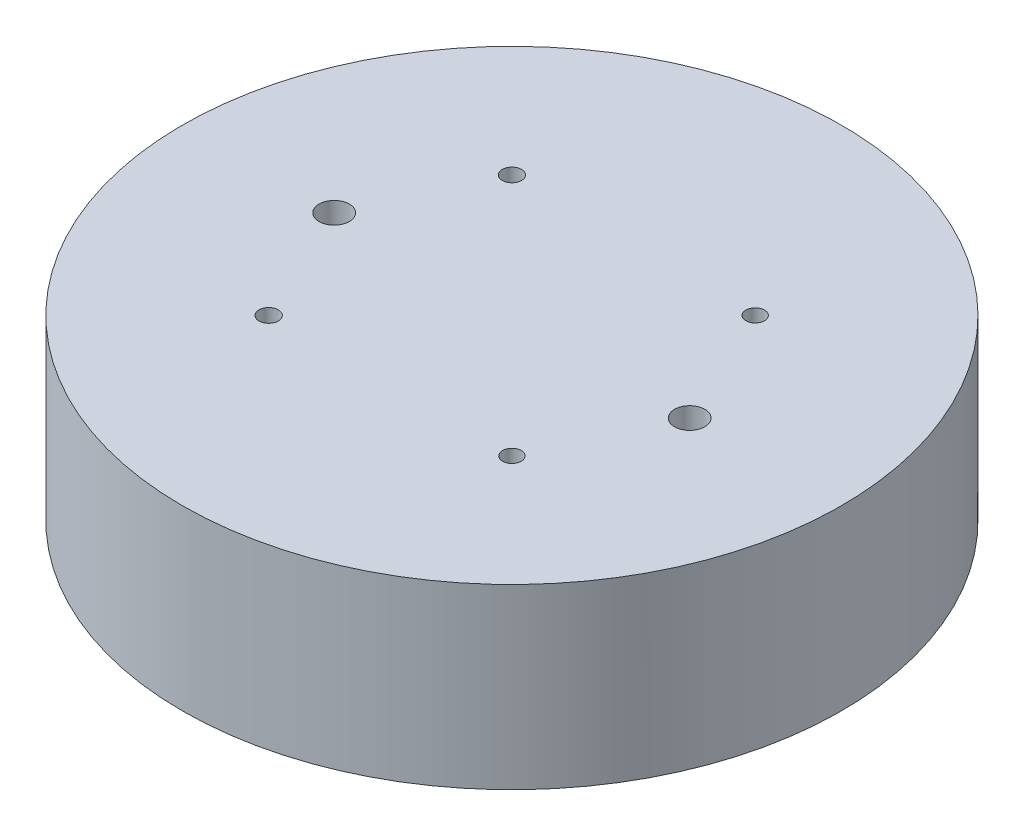
SolidWorks part; units mm, degrees
ref_plane "Front Plane" through (0, 0, 0) normal (0, 0, 1) x (1, 0, 0)
ref_plane "Top Plane" through (0, 0, 0) normal (0, 1, 0) x (1, 0, 0)
ref_plane "Right Plane" through (0, 0, 0) normal (1, 0, 0) x (0, 0, -1)
sketch "Sketch2" plane through (0, 0, 0) normal (0, 1, 0) x (1, 0, 0)
  line L0 (0, 0) -> (0, 56.515)
  circle A0 centre (0, 0) radius 51.435
  circle A1 centre (0, 0) radius 56.515
  circle A2 centre (0, 0) radius 47.2017
  circle A3 centre (0, 0) radius 42.1217
  dimension "D1" = 14.3933
  dimension "D2" = 5.08
  dimension "D3" = 4.2333
  dimension "D4" = 5.08
  dimension "D5" = 102.87
  dimension "D6" = 94.4033
extrude "Boss-Extrude1" add sketch "Sketch2" along normal blind 15.24 contours A1 A0 | A2 A3
sketch "Sketch3" plane through (0, 15.24, 0) normal (0, 1, 0) x (1, 0, 0)
  circle A0 centre (0, 0) radius 56.515
  dimension "D1" = 113.03
extrude "Boss-Extrude2" add sketch "Sketch3" along normal blind 15.24
sketch "Sketch4" plane through (0, 30.48, 0) normal (0, 1, 0) x (1, 0, 0)
  line L0 (0, 37.845) -> (0, -37.845) construction
  line L1 (37.845, 0) -> (-37.845, 0) construction
  line L2 (26.7605, 26.7605) -> (-26.7605, -26.7605) construction
  line L3 (-26.7605, 26.7605) -> (26.7605, -26.7605) construction
  circle A0 centre (0, 0) radius 37.845 construction
  circle A1 centre (0, 0) radius 29.5 construction
  circle A2 centre (20.8597, 20.8597) radius 1.6
  circle A3 centre (20.8597, -20.8597) radius 1.6
  circle A4 centre (-20.8597, -20.8597) radius 1.6588
  circle A5 centre (-20.8597, 20.8597) radius 1.651
  point P7 (0, 0)
  point P10 (0, 0)
  point P13 (0, 0)
  point P16 (0, 0)
  dimension "D1" = 75.69
  dimension "D2" = 59
  dimension "D3" = 45
  dimension "D4" = 45
  dimension "D5" = 3.2
  dimension "D6" = 3.2
  dimension "D7" = 3.3175
  dimension "D8" = 3.302
extrude "Cut-Extrude1" cut sketch "Sketch4" against normal through all both and the other way through all
sketch "Sketch5" plane through (0, 0, 0) normal (0, -1, 0) x (-1, 0, 0)
  line L0 (0, 0) -> (0, 29.5)
  line L1 (13.9476, 25) -> (-13.9476, 25)
  circle A1 centre (0, 0) radius 37.845
  circle A2 centre (0, 0) radius 29.5
  arc A3 (-13.9476, 54.7669) -> (13.9476, 54.7669) centre (0, 0) cw
  circle A4 centre (0, 0) radius 56.515 construction
  point P9 (0, 25)
  dimension "D1" = 75.69
  dimension "D2" = 59
  dimension "D3" = 25
  dimension "D4" = 31.515
ref_plane "Plane1" through (0, 0, -56.515) normal (0, 0, 1) x (1, 0, 0)
ref_plane "Plane3" through (0, 0, -47.244) normal (0, 0, 1) x (1, 0, 0)
ref_plane "Plane4" through (17.78, 0, 0) normal (1, 0, 0) x (0, 0, -1)
sketch "Sketch13" plane through (0, 0, -56.515) normal (0, 0, 1) x (1, 0, 0)
  line L0 (0, 0) -> (0, 32.5704) construction
sketch "Sketch14" plane through (0, 0, -56.515) normal (0, 0, 1) x (1, 0, 0)
  line L0 (0, 0) -> (0, 30.48) construction
  line L1 (-56.515, 0) -> (56.515, 0) construction
  line L2 (56.515, 30.48) -> (-56.515, 30.48) construction
  line L3 (0, 15.24) -> (-5.7214, 15.24) construction
  circle A0 centre (0, 5.08) radius 10
  dimension "D3" = 20
  dimension "D1" = 15.24
  dimension "D2" = 10.16
extrude "Cut-Extrude7" cut sketch "Sketch14" along normal blind 19.558
sketch "Sketch16" plane through (0, 0, -56.515) normal (0, 0, 1) x (1, 0, 0)
  line L0 (0, 0) -> (0, 15.24) construction
  line L1 (0, 5.08) -> (0, 15.24) construction
  line L3 (0, 0) -> (0, 1.27)
  line L4 (9.2458, 1.27) -> (-9.2458, 1.27)
  arc A1 (9.2458, 1.27) -> (-9.2458, 1.27) centre (0, 5.08) ccw
  point P12 (0, 1.27)
  dimension "D1" = 10.16
  dimension "D2" = 1.27
  dimension "D3" = 15.24
extrude "Extrude-Thin1" add sketch "Sketch16" along normal blind 15.24 thin thin type one direction wall 1.27
sketch "Sketch20" plane through (0, 0, 0) normal (0, -1, 0) x (-1, 0, 0)
  circle A0 centre (0, 0) radius 56.515
extrude "Cut-Extrude-Thin3" cut sketch "Sketch20" against normal blind 15.748 thin
sketch "Sketch21" plane through (0, 0, -56.515) normal (0, 0, 1) x (1, 0, 0)
  line L0 (-9.3037, 0) -> (-9.2458, 1.27)
  line L1 (-56.515, 0) -> (56.515, 0) construction
  line L2 (-9.2458, 1.27) -> (9.2458, 1.27)
  line L3 (9.2458, 1.27) -> (-9.2458, 1.27) construction
  line L4 (9.2458, 1.27) -> (9.2458, 0)
  line L5 (9.2458, 0) -> (-9.3037, 0)
  arc A0 (8.6136, 0) -> (8.4029, 10.5013) centre (0, 5.08) ccw construction
extrude "Cut-Extrude12" cut sketch "Sketch21" along normal blind 15.748
sketch "Sketch24" plane through (0, 30.48, 0) normal (0, 1, 0) x (1, 0, 0)
  line L0 (-39.5661, 40.3543) -> (40.3543, -39.5661) construction
  line L1 (0, 56.515) -> (0, -56.515) construction
  circle A2 centre (0, 0) radius 56.515 construction
  circle A3 centre (30.48, 0) radius 2.6
  circle A5 centre (-30.48, 0) radius 2.6
  point P22 (0, 0)
  dimension "D1" = 45
  dimension "D2" = 5.2
  dimension "D3" = 5.2
sketch "Sketch25" plane through (0, 15.24, 0) normal (0, -1, 0) x (-1, 0, 0)
  circle A3 centre (30.48, 0) radius 7.5
  circle A5 centre (-30.48, 0) radius 7.5
  point P24 (0, 0)
  dimension "D1" = 15
  dimension "D2" = 15
extrude "Cut-Extrude15" cut sketch "Sketch24" against normal blind 7.62
extrude "Cut-Extrude16" cut sketch "Sketch25" against normal blind 7.62
sketch "Sketch26" plane through (0, 30.48, 0) normal (0, 1, 0) x (1, 0, 0)
  line L1 (185.787, -10) -> (-68.213, -10)
  line L2 (185.787, -10) -> (185.787, 10)
  line L3 (185.787, 10) -> (-68.213, 10)
  line L5 (-68.213, -10) -> (-240.3713, -10)
  line L7 (-68.213, 10) -> (-240.3713, 10)
  line L8 (-240.3713, -10) -> (-240.3713, 10)
  dimension "D1" = 20
  dimension "D2" = 10
  dimension "D3" = 254
